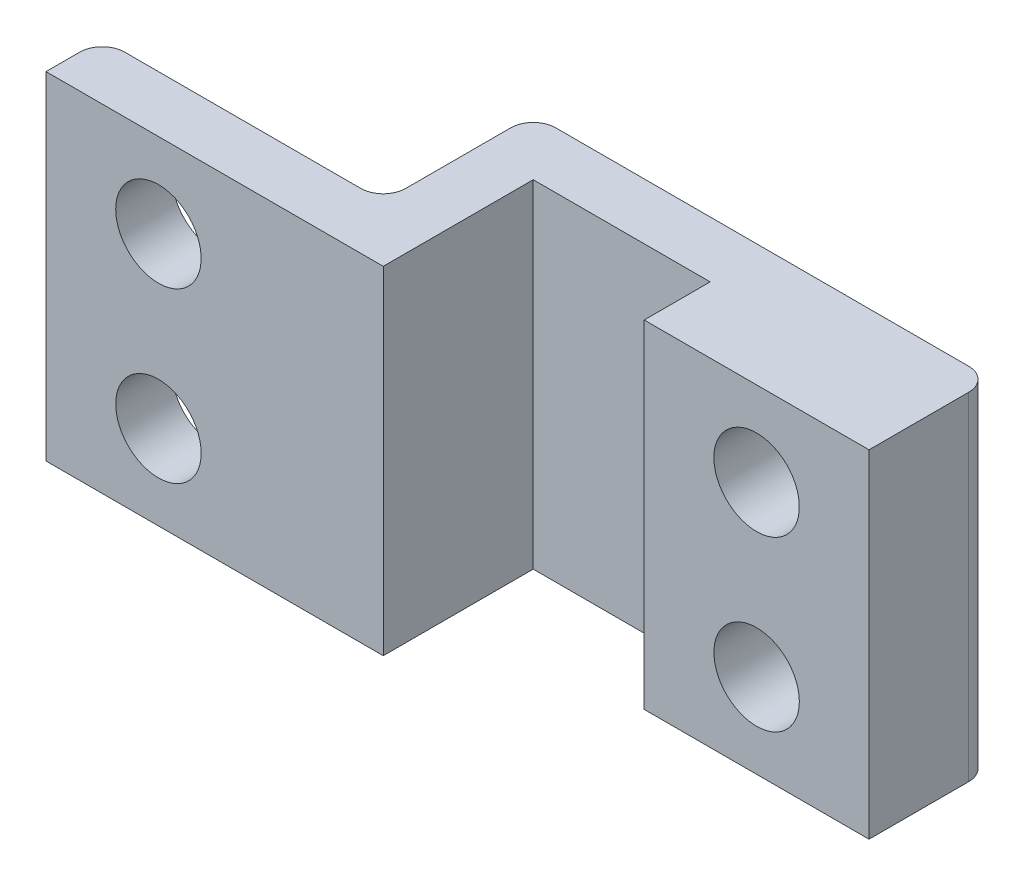
SolidWorks part; units mm, degrees
ref_plane "Front Plane" through (0, 0, 0) normal (0, 0, 1) x (1, 0, 0)
ref_plane "Top Plane" through (0, 0, 0) normal (0, 1, 0) x (1, 0, 0)
ref_plane "Right Plane" through (0, 0, 0) normal (1, 0, 0) x (0, 0, -1)
sketch "Sketch1" plane through (0, 0, 0) normal (0, 0, 1) x (1, 0, 0)
  line L1 (-19.05, -19.05) -> (19.05, -19.05)
  line L2 (-19.05, -19.05) -> (-19.05, 19.05)
  line L3 (-19.05, 19.05) -> (19.05, 19.05)
  line L4 (19.05, -19.05) -> (19.05, 19.05)
  line L5 (-19.05, -19.05) -> (19.05, 19.05) construction
  line L6 (-19.05, 19.05) -> (19.05, -19.05) construction
  point P0 (0, 0)
  dimension "D1" = 38.1
  dimension "D2" = 38.1
extrude "Boss-Extrude1" add sketch "Sketch1" against normal blind 6.35
sketch "Sketch2" plane through (0, 0, -6.35) normal (0, 0, -1) x (-1, 0, 0)
  line L0 (19.05, -19.05) -> (-19.05, -19.05) construction
  line L1 (-19.05, 19.05) -> (-12.7, 19.05)
  line L2 (-19.05, 19.05) -> (-19.05, -19.05)
  line L3 (-19.05, -19.05) -> (-12.7, -19.05)
  line L4 (-12.7, 19.05) -> (-12.7, -19.05)
  dimension "D1" = 6.35
extrude "Boss-Extrude2" add sketch "Sketch2" along normal blind 16.9418
sketch "Sketch4" plane through (19.05, 0, 0) normal (1, 0, 0) x (0, 0, -1)
  line L0 (23.2918, -19.05) -> (0, -19.05) construction
  line L1 (23.2918, 19.05) -> (16.9418, 19.05)
  line L2 (23.2918, 19.05) -> (23.2918, -19.05)
  line L3 (23.2918, -19.05) -> (16.9418, -19.05)
  line L4 (16.9418, 19.05) -> (16.9418, -19.05)
  dimension "D1" = 6.35
extrude "Boss-Extrude3" add sketch "Sketch4" along normal blind 45.3898
sketch "Sketch5" plane through (0, 0, -16.9418) normal (0, 0, 1) x (1, 0, 0)
  line L0 (64.4398, -19.05) -> (19.05, -19.05) construction
  line L1 (64.4398, 19.05) -> (39.0398, 19.05)
  line L2 (64.4398, 19.05) -> (64.4398, -19.05)
  line L3 (64.4398, -19.05) -> (39.0398, -19.05)
  line L4 (39.0398, 19.05) -> (39.0398, -19.05)
  dimension "D1" = 25.4
extrude "Boss-Extrude4" add sketch "Sketch5" along normal blind 7.4549
sketch "Sketch6" plane through (0, 0, -6.35) normal (0, 0, -1) x (-1, 0, 0)
  line L0 (19.05, 0) -> (-12.7, 0) construction
  line L1 (19.05, 19.05) -> (19.05, -19.05) construction
  line L2 (-12.7, -19.05) -> (-12.7, 19.05) construction
  line L3 (-12.7, 19.05) -> (19.05, 19.05) construction
  circle A0 centre (6.35, 9.525) radius 4.826
  circle A1 centre (6.35, -9.525) radius 4.826
  dimension "D1" = 12.7
  dimension "D3" = 9.652
  dimension "D2" = 9.525
extrude "Cut-Extrude1" cut sketch "Sketch6" against normal through all
sketch "Sketch8" plane through (0, 0, -9.4869) normal (0, 0, 1) x (1, 0, 0)
  line L0 (39.0398, 0) -> (64.4398, 0) construction
  line L1 (39.0398, 19.05) -> (39.0398, -19.05) construction
  line L2 (64.4398, -19.05) -> (64.4398, 19.05) construction
  circle A0 centre (51.7398, -9.525) radius 4.826
  circle A1 centre (51.7398, 9.525) radius 4.826
  dimension "D1" = 9.525
  dimension "D3" = 9.652
  dimension "D2" = 12.7
extrude "Cut-Extrude2" cut sketch "Sketch8" against normal through all
fillet "Fillet7" radius 2.54 4 edges at (-19.05, 0, -6.35) (12.7, 0, -6.35) (12.7, 0, -23.2918) (64.4398, 0, -23.2918)
